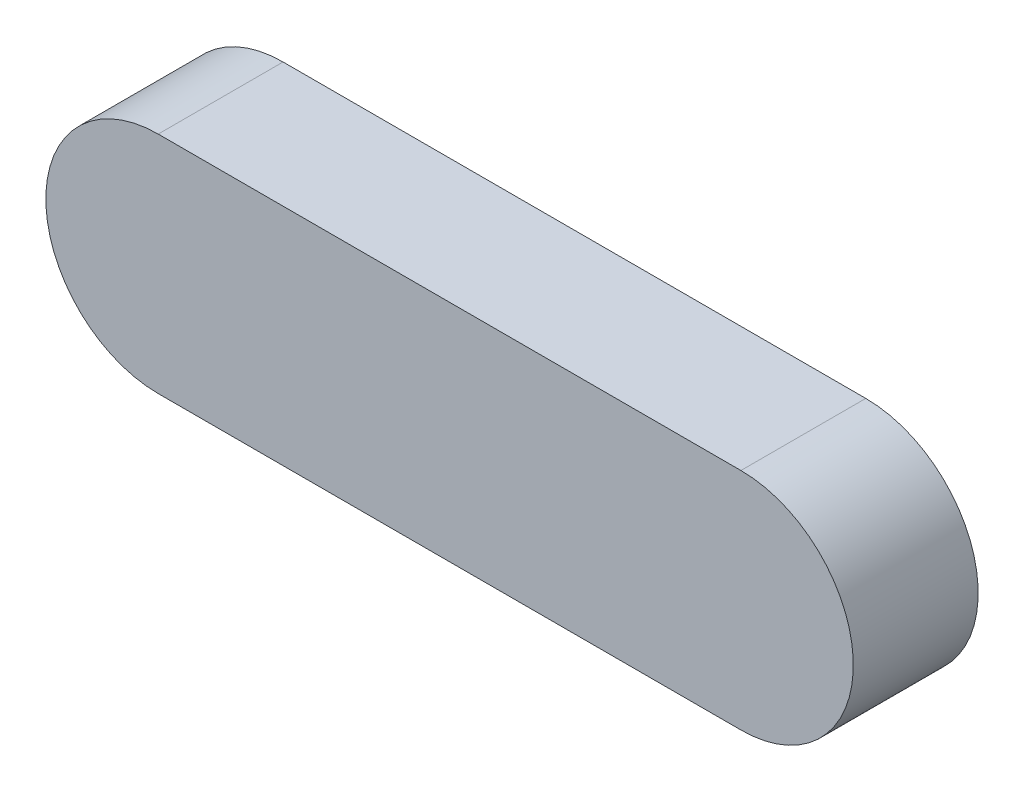
SolidWorks part; units mm, degrees
ref_plane "Front Plane" through (0, 0, 0) normal (0, 0, 1) x (1, 0, 0)
ref_plane "Top Plane" through (0, 0, 0) normal (0, 1, 0) x (1, 0, 0)
ref_plane "Right Plane" through (0, 0, 0) normal (1, 0, 0) x (0, 0, -1)
sketch "Sketch1" plane through (0, 0, 0) normal (0, 0, 1) x (1, 0, 0)
  line L0 (50, 212.065) -> (-20, 212.065) construction
  line L7 (50, 198.565) -> (-20, 198.565)
  line L8 (50, 225.565) -> (-20, 225.565)
  arc A0 (50, 198.565) -> (50, 225.565) centre (50, 212.065) ccw
  arc A1 (-20, 225.565) -> (-20, 198.565) centre (-20, 212.065) ccw
  point P0 (15, 178.465)
  point P7 (15, 212.065)
  dimension "D2" = 27
  dimension "D4" = 33.6
  dimension "D5" = 70
extrude "Extrude1" add sketch "Sketch1" along normal blind 15
sketch "Sketch2" plane through (0, 0, 0) normal (0, 0, -1) x (-1, 0, 0)
  circle A0 centre (-15, 212.065) radius 10
  arc A1 (20, 198.565) -> (20, 225.565) centre (20, 212.065) ccw construction
  point P2 (33.5, 212.065)
  dimension "D1" = 0
extrude "Extrude2" cut sketch "Sketch2" against normal blind 10
